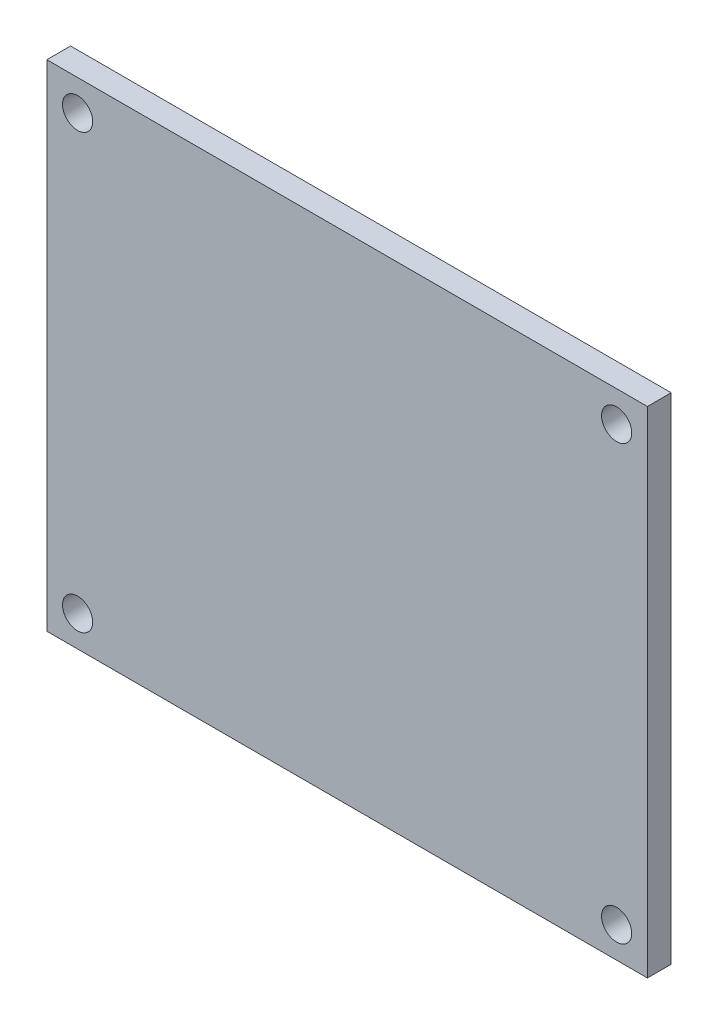
SolidWorks part; units mm, degrees
ref_plane "Front Plane" through (0, 0, 0) normal (0, 0, 1) x (1, 0, 0)
ref_plane "Top Plane" through (0, 0, 0) normal (0, 1, 0) x (1, 0, 0)
ref_plane "Right Plane" through (0, 0, 0) normal (1, 0, 0) x (0, 0, -1)
sketch "Sketch1" plane through (0, 0, 0) normal (0, 0, 1) x (1, 0, 0)
  line L0 (0, 0) -> (-50.55, 0)
  line L1 (0, 0) -> (0, 41.66)
  line L2 (-50.55, 0) -> (-50.55, 41.66)
  line L3 (-50.55, 41.66) -> (0, 41.66)
  line L4 (-50.55, 0) -> (-48.55, 0)
  line L5 (0, 0) -> (-2, 0)
  line L6 (-50.55, 41.66) -> (-48.55, 41.66)
  line L7 (0, 41.66) -> (-2, 41.66)
  line L8 (-2, 41.66) -> (-2, 39.66)
  line L9 (-48.55, 41.66) -> (-48.55, 39.66)
  line L10 (-48.55, 0) -> (-48.55, 2)
  line L11 (-2, 0) -> (-2, 2)
  line L12 (-48.55, 2) -> (-2, 2)
  line L13 (-48.55, 2) -> (-48.55, 39.66)
  line L14 (-48.55, 39.66) -> (-2, 39.66)
  line L15 (-2, 39.66) -> (-2, 2)
  dimension "D1" = 50.55
  dimension "D2" = 41.66
  dimension "D3" = 2
  dimension "D4" = 2
  dimension "D5" = 2
  dimension "D6" = 2
  dimension "D7" = 2
  dimension "D8" = 2
  dimension "D9" = 2
  dimension "D10" = 2
extrude "Boss-Extrude1" add sketch "Sketch1" along normal blind 2 contours L9 L14 L8 L3 | L8 L15 L11 L0 L1 L3 | L10 L13 L9 L3 L2 L0 | L12 L10 L0 L11
sketch "Sketch11" plane through (0, 0, 0) normal (0, 0, -1) x (-1, 0, 0)
  line L1 (2, 39.66) -> (48.55, 39.66)
  line L2 (2, 39.66) -> (2, 2)
  line L3 (2, 2) -> (48.55, 2)
  line L4 (48.55, 39.66) -> (48.55, 2)
extrude "Boss-Extrude3" add sketch "Sketch11" against normal blind 2
sketch "Sketch12" plane through (0, 0, 0) normal (0, 0, -1) x (-1, 0, 0)
  line L0 (0, 41.66) -> (0, 39.07)
  line L1 (0, 0) -> (0, 41.66) construction
  line L2 (0, 39.07) -> (2.59, 39.07)
  line L3 (50.55, 41.66) -> (47.96, 41.66)
  line L4 (50.55, 41.66) -> (0, 41.66) construction
  line L5 (47.96, 41.66) -> (47.96, 39.07)
  line L6 (0, 0) -> (0, 2.59)
  line L7 (0, 0) -> (2.59, 0)
  line L8 (0, 0) -> (50.55, 0) construction
  line L9 (2.59, 0) -> (2.59, 2.59)
  line L10 (50.55, 0) -> (47.96, 0)
  line L11 (47.96, 0) -> (47.96, 2.59)
  circle A0 centre (2.59, 39.07) radius 1.27
  circle A1 centre (47.96, 39.07) radius 1.27
  circle A2 centre (2.59, 2.59) radius 1.27
  circle A3 centre (47.96, 2.59) radius 1.27
  dimension "D3" = 2.54
  dimension "D6" = 2.54
  dimension "D9" = 2.59
  dimension "D11" = 2.54
  dimension "D1" = 2.59
  dimension "D2" = 2.59
  dimension "D4" = 2.59
  dimension "D5" = 2.59
  dimension "D7" = 2.59
  dimension "D8" = 2.59
  dimension "D10" = 2.59
extrude "Cut-Extrude6" cut sketch "Sketch12" against normal blind 2 contours A1 | A3 | A0 | A2
